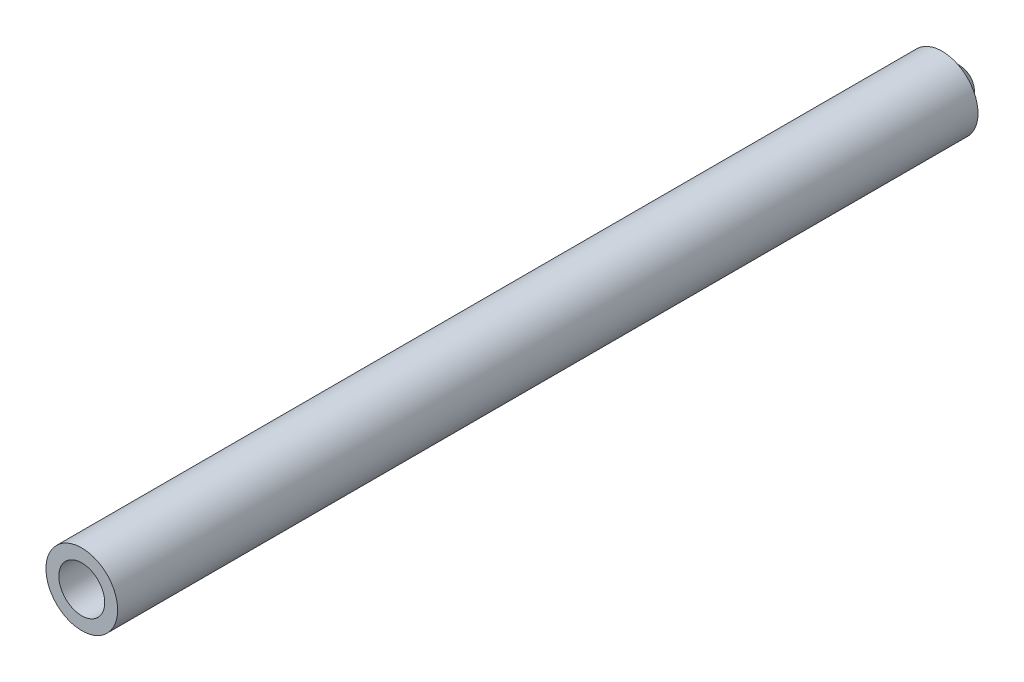
SolidWorks part; units mm, degrees
ref_plane "Front Plane" through (0, 0, 0) normal (0, 0, 1) x (1, 0, 0)
ref_plane "Top Plane" through (0, 0, 0) normal (0, 1, 0) x (1, 0, 0)
ref_plane "Right Plane" through (0, 0, 0) normal (1, 0, 0) x (0, 0, -1)
sketch "Sketch5" plane through (0, 0, 0) normal (0, 0, 1) x (1, 0, 0)
  circle A0 centre (0, 0) radius 62.5
  circle A1 centre (0, 0) radius 40
  dimension "D1" = 125
  dimension "D2" = 80
extrude "Boss-Extrude3" add sketch "Sketch5" along normal blind 1500
sketch "Sketch7" plane through (0, 0, 0) normal (0, 0, -1) x (-1, 0, 0)
  line L0 (-40, 0) -> (40, 0)
  circle A0 centre (0, 0) radius 40 construction
  arc A1 (-40, 0) -> (40, 0) centre (0, 0) cw
revolve "Revolve1" add sketch "Sketch7" angle 360 about L0
